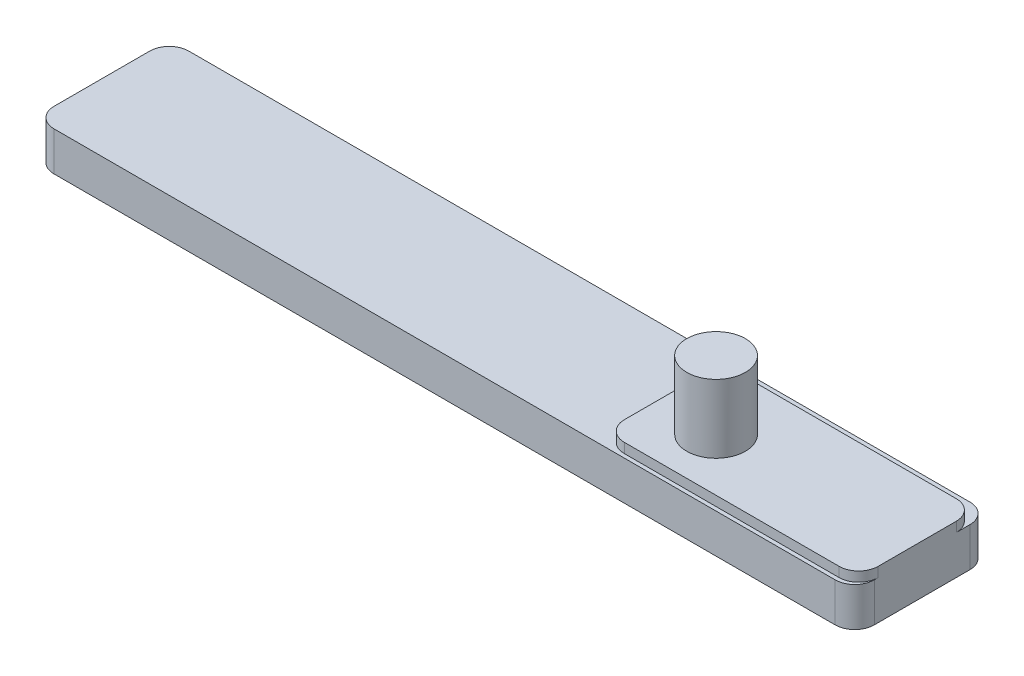
SolidWorks part; units mm, degrees
ref_plane "前视基准面" through (0, 0, 0) normal (0, 0, 1) x (1, 0, 0)
ref_plane "上视基准面" through (0, 0, 0) normal (0, 1, 0) x (1, 0, 0)
ref_plane "右视基准面" through (0, 0, 0) normal (1, 0, 0) x (0, 0, -1)
other "Configuration Table"
sketch "草图1" plane through (0, 0, 0) normal (0, 1, 0) x (1, 0, 0)
  line L1 (0, 0) -> (42, 0)
  line L2 (0, 0) -> (0, 7.4)
  line L3 (0, 7.4) -> (42, 7.4)
  line L4 (42, 0) -> (42, 7.4)
  line L5 (0, 0) -> (42, 7.4) construction
  line L6 (0, 7.4) -> (42, 0) construction
  point P4 (21, 3.7)
  dimension "D1" = 7.4
  dimension "D2" = 42
extrude "凸台-拉伸1" add sketch "草图1" along normal blind 2.5
sketch "草图2" plane through (0, 2.5, 0) normal (0, 1, 0) x (1, 0, 0)
  line L0 (0, 0) -> (42, 0) construction
  line L3 (42, 0) -> (42, 7.4) construction
  circle A0 centre (32, 3.4) radius 1.5
  dimension "D1" = 3
  dimension "D2" = 3.4
  dimension "D3" = 10
extrude "凸台-拉伸2" add sketch "草图2" along normal blind 3.5
sketch "草图3" plane through (0, 2.5, 0) normal (0, 1, 0) x (1, 0, 0)
  line L0 (0, 0) -> (42, 0) construction
  line L1 (0, 7.4) -> (29, 7.4)
  line L2 (0, 7.4) -> (0, 0)
  line L3 (0, 0) -> (29, 0)
  line L4 (29, 7.4) -> (29, 0)
  line L5 (0, 7.4) -> (29, 0) construction
  line L6 (0, 0) -> (29, 7.4) construction
  point P4 (14.5, 3.7)
  dimension "D1" = 29
extrude "切除-拉伸1" cut sketch "草图3" against normal blind 0.5
sketch "草图4" plane through (0, 2.5, 0) normal (0, 1, 0) x (1, 0, 0)
  line L0 (42, 0) -> (42, 7.4) construction
  line L1 (29, 7.4) -> (42, 7.4)
  line L2 (29, 7.4) -> (29, 6.7)
  line L3 (29, 6.7) -> (42, 6.7)
  line L4 (42, 7.4) -> (42, 6.7)
  line L5 (29, 7.4) -> (42, 6.7) construction
  line L6 (29, 6.7) -> (42, 7.4) construction
  line L8 (29, 0) -> (42, 0)
  line L9 (29, 0) -> (29, 0.7)
  line L10 (29, 0.7) -> (42, 0.7)
  line L11 (42, 0) -> (42, 0.7)
  line L12 (29, 0) -> (42, 0.7) construction
  line L13 (29, 0.7) -> (42, 0) construction
  point P4 (35.5, 7.05)
  point P12 (35.5, 0.35)
  dimension "D1" = 0.7
  dimension "D2" = 0.7
extrude "切除-拉伸2" cut sketch "草图4" against normal up to surface (0.5 mm away) up to face at (14.5, 2, -3.7)
sketch "草图5" plane through (0, 2, 0) normal (0, 1, 0) x (1, 0, 0)
  line L0 (42, 0.7) -> (42, 0) construction
  line L1 (0, 0) -> (42, 0)
  line L2 (0, 0) -> (0, 0.5)
  line L3 (0, 0.5) -> (42, 0.5)
  line L4 (42, 0) -> (42, 0.5)
  line L5 (0, 0) -> (42, 0.5) construction
  line L6 (0, 0.5) -> (42, 0) construction
  point P4 (21, 0.25)
  point P7 (0, 0)
  point P8 (42, 0.5)
  dimension "D1" = 0.5
extrude "切除-拉伸3" cut sketch "草图5" against normal up to next
fillet "圆角1" radius 1 6 edges at (42, 2.25, -0.7) (42, 2.25, -6.7) (0, 1, -7.4) (29, 2.25, -0.7) (29, 2.25, -6.7) (0, 1, -0.5)
fillet "圆角2" radius 1 2 edges at (42, 1, -7.4) (42, 1, -0.5)
